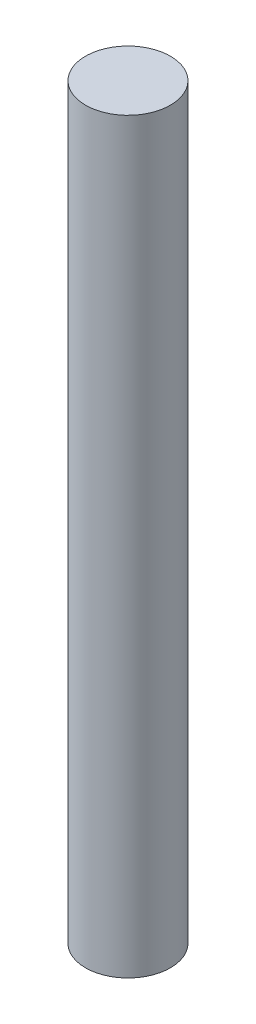
SolidWorks part; units mm, degrees
material "AISI 304"
ref_plane "Front Plane" through (0, 0, 0) normal (0, 0, 1) x (1, 0, 0)
ref_plane "Top Plane" through (0, 0, 0) normal (0, 1, 0) x (1, 0, 0)
ref_plane "Right Plane" through (0, 0, 0) normal (1, 0, 0) x (0, 0, -1)
sketch "Sketch1" plane through (0, 0, 0) normal (0, 1, 0) x (1, 0, 0)
  circle A0 centre (0, 0) radius 7.9375
  dimension "D1" = 15.875
extrude "Boss-Extrude1" add sketch "Sketch1" along normal blind 139.7
